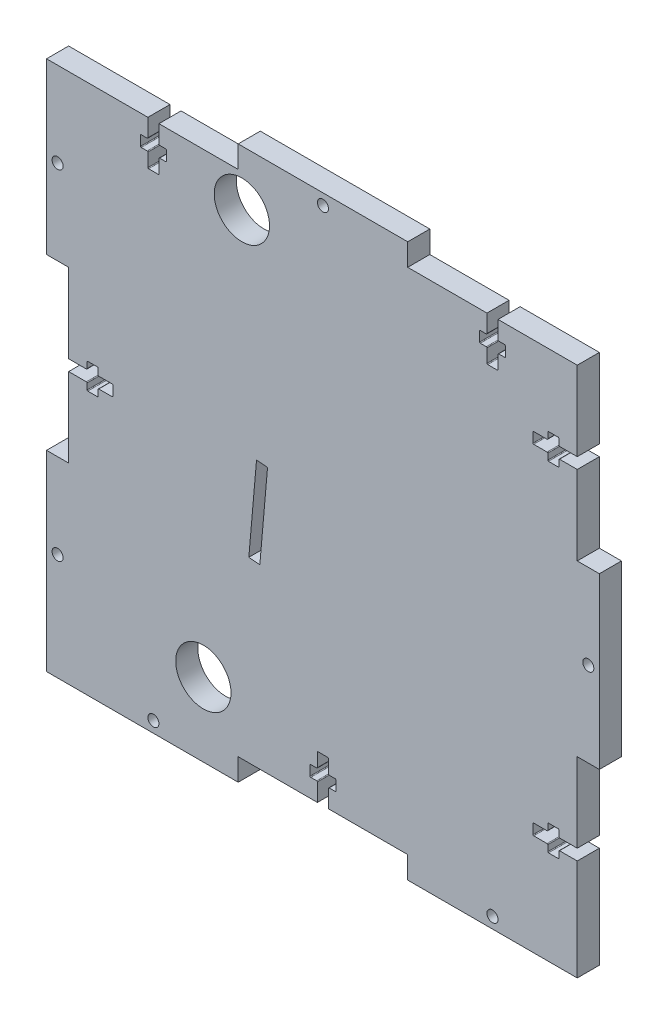
SolidWorks part; units mm, degrees
ref_plane "Front Plane" through (0, 0, 0) normal (0, 0, 1) x (1, 0, 0)
ref_plane "Top Plane" through (0, 0, 0) normal (0, 1, 0) x (1, 0, 0)
ref_plane "Right Plane" through (0, 0, 0) normal (1, 0, 0) x (0, 0, -1)
sketch "Sketch1" plane through (0, 0, 0) normal (0, 0, 1) x (1, 0, 0)
  line L0 (-69, 69) -> (-23, 69)
  line L5 (-75, -75) -> (75, -75) construction
  line L6 (-75, -75) -> (-75, 75) construction
  line L7 (-75, 75) -> (75, 75) construction
  line L8 (75, -75) -> (75, 75) construction
  line L9 (75, 23) -> (69, 23)
  line L10 (69, -23) -> (75, -23)
  line L11 (-69, -69) -> (69, -69) construction
  line L12 (-69, -69) -> (-69, 69) construction
  line L13 (-69, 69) -> (69, 69) construction
  line L14 (69, -69) -> (69, 69) construction
  line L15 (-69, -69) -> (69, 69) construction
  line L16 (69, -69) -> (69, -23)
  line L17 (-23, 69) -> (-23, 75)
  line L18 (-23, 75) -> (23, 75)
  line L19 (23, 75) -> (23, 69)
  line L20 (23, 69) -> (69, 69)
  line L21 (75, -23) -> (75, 23)
  line L22 (69, 23) -> (69, 69)
  line L23 (-75, 23) -> (-69, 23)
  line L24 (-69, 69) -> (-75, 69)
  line L25 (-75, 69) -> (-75, 23)
  line L26 (69, -69) -> (69, -75)
  line L27 (69, -75) -> (23, -75)
  line L28 (23, -75) -> (23, -69)
  line L29 (23, -69) -> (-23, -69)
  line L30 (-23, -69) -> (-23, -75)
  line L31 (-23, -75) -> (-69, -75)
  line L32 (-69, -75) -> (-69, -69) construction
  line L33 (-69, 23) -> (-69, -23)
  line L34 (-69, -23) -> (-75, -23)
  line L35 (-75, -23) -> (-75, -69)
  line L36 (-75, -69) -> (-69, -69) construction
  line L37 (-46, 69) -> (-46, -75) construction
  line L38 (-69, 69) -> (69, -69) construction
  line L39 (-75, -75) -> (-69, -75)
  line L40 (-75, -75) -> (-75, -69)
  point P0 (0, 0)
  point P6 (-7, -7)
  point P26 (0, -75)
  point P27 (-75, 0)
  dimension "D1" = 150
  dimension "D2" = 150
  dimension "D5" = 46
  dimension "D3" = 6
  dimension "D6" = 6
  dimension "D7" = 6
extrude "Box Side" add sketch "Sketch1" along normal blind 6
sketch "Sketch2" plane through (0, 0, 6) normal (0, 0, 1) x (1, 0, 0)
  line L0 (23, 72) -> (-23, 72) construction
  line L1 (23, 75) -> (23, 69) construction
  line L2 (-23, 69) -> (-23, 75) construction
  line L3 (-46, 69) -> (-46, -75) construction
  line L5 (0, 75) -> (0, 69) construction
  line L6 (-23, 75) -> (23, 75) construction
  line L7 (-69, 69) -> (69, 69) construction
  line L16 (-46, 69) -> (-46, -75) construction
  line L21 (0, -69) -> (0, 69) construction
  line L35 (-69, 69) -> (-23, 69) construction
  line L36 (-44.5, 69) -> (-44.5, 64.2)
  line L37 (-44.3, 64) -> (-42.7, 64)
  line L38 (-42.5, 63.8) -> (-42.5, 61.2)
  line L39 (-42.7, 61) -> (-44.3, 61)
  line L40 (-44.5, 60.8) -> (-44.5, 57.2)
  line L46 (-44.7, 57) -> (-47.3, 57)
  line L48 (-44.5, 69) -> (-47.5, 69)
  line L51 (-47.5, 60.8) -> (-47.5, 57.2)
  line L52 (-49.3, 61) -> (-47.7, 61)
  line L53 (-49.5, 63.8) -> (-49.5, 61.2)
  line L54 (-47.7, 64) -> (-49.3, 64)
  line L55 (-47.5, 69) -> (-47.5, 64.2)
  line L56 (47.5, 69) -> (47.5, 64.2)
  line L57 (47.7, 64) -> (49.3, 64)
  line L58 (49.5, 63.8) -> (49.5, 61.2)
  line L59 (49.3, 61) -> (47.7, 61)
  line L60 (47.5, 60.8) -> (47.5, 57.2)
  line L61 (44.5, 69) -> (47.5, 69)
  line L62 (44.7, 57) -> (47.3, 57)
  line L63 (44.5, 60.8) -> (44.5, 57.2)
  line L64 (42.7, 61) -> (44.3, 61)
  line L65 (42.5, 63.8) -> (42.5, 61.2)
  line L66 (44.3, 64) -> (42.7, 64)
  line L67 (44.5, 69) -> (44.5, 64.2)
  line L68 (-69, -69) -> (69, 69) construction
  line L69 (-69, -69) -> (69, 69) construction
  line L70 (75, 0) -> (69, 0) construction
  line L71 (72, 23) -> (72, -23) construction
  line L72 (69, 44.5) -> (64.2, 44.5)
  line L73 (64, 44.3) -> (64, 42.7)
  line L74 (63.8, 42.5) -> (61.2, 42.5)
  line L75 (61, 42.7) -> (61, 44.3)
  line L76 (60.8, 44.5) -> (57.2, 44.5)
  line L77 (57, 44.7) -> (57, 47.3)
  line L78 (69, 44.5) -> (69, 47.5)
  line L79 (60.8, 47.5) -> (57.2, 47.5)
  line L80 (61, 49.3) -> (61, 47.7)
  line L81 (63.8, 49.5) -> (61.2, 49.5)
  line L82 (64, 47.7) -> (64, 49.3)
  line L83 (69, 47.5) -> (64.2, 47.5)
  line L84 (69, -47.5) -> (64.2, -47.5)
  line L85 (64, -47.7) -> (64, -49.3)
  line L86 (63.8, -49.5) -> (61.2, -49.5)
  line L87 (61, -49.3) -> (61, -47.7)
  line L88 (60.8, -47.5) -> (57.2, -47.5)
  line L89 (69, -44.5) -> (69, -47.5)
  line L90 (57, -44.7) -> (57, -47.3)
  line L91 (60.8, -44.5) -> (57.2, -44.5)
  line L92 (61, -42.7) -> (61, -44.3)
  line L93 (63.8, -42.5) -> (61.2, -42.5)
  line L94 (64, -44.3) -> (64, -42.7)
  line L95 (69, -44.5) -> (64.2, -44.5)
  line L120 (-69, 69) -> (69, -69) construction
  line L121 (-69, 69) -> (69, -69) construction
  line L122 (-1.5, -69) -> (1.5, -69)
  line L123 (-23, -69) -> (23, -69) construction
  line L124 (1.5, -69) -> (1.5, -64.2)
  line L125 (1.7, -64) -> (3.3, -64)
  line L126 (3.5, -63.8) -> (3.5, -61.2)
  line L127 (3.3, -61) -> (1.7, -61)
  line L128 (1.5, -60.8) -> (1.5, -57.2)
  line L129 (1.3, -57) -> (-1.3, -57)
  line L130 (-1.5, -60.8) -> (-1.5, -57.2)
  line L131 (-3.3, -61) -> (-1.7, -61)
  line L132 (-3.5, -63.8) -> (-3.5, -61.2)
  line L133 (-1.7, -64) -> (-3.3, -64)
  line L134 (-1.5, -69) -> (-1.5, -64.2)
  line L135 (-69, -1.5) -> (-64.2, -1.5)
  line L136 (-64, -1.7) -> (-64, -3.3)
  line L137 (-63.8, -3.5) -> (-61.2, -3.5)
  line L138 (-61, -3.3) -> (-61, -1.7)
  line L139 (-60.8, -1.5) -> (-57.2, -1.5)
  line L140 (-57, 1.3) -> (-57, -1.3)
  line L141 (-60.8, 1.5) -> (-57.2, 1.5)
  line L142 (-61, 3.3) -> (-61, 1.7)
  line L143 (-63.8, 3.5) -> (-61.2, 3.5)
  line L144 (-64, 1.7) -> (-64, 3.3)
  line L145 (-69, 1.5) -> (-64.2, 1.5)
  line L146 (-69, -1.5) -> (-69, 1.5)
  line L147 (-69, -72) -> (-23, -72) construction
  line L148 (-23, 69) -> (-75, 69) construction
  line L149 (-23, -75) -> (-23, -69) construction
  line L150 (-69, -69) -> (-69, -75) construction
  line L151 (-75, -75) -> (-23, -75) construction
  circle A0 centre (0, 72) radius 1.5
  arc A1 (-44.5, 57.2) -> (-44.7, 57) centre (-44.7, 57.2) cw
  arc A2 (-44.3, 61) -> (-44.5, 60.8) centre (-44.3, 60.8) ccw
  arc A3 (-42.5, 61.2) -> (-42.7, 61) centre (-42.7, 61.2) cw
  arc A4 (-42.7, 64) -> (-42.5, 63.8) centre (-42.7, 63.8) cw
  arc A5 (-44.5, 64.2) -> (-44.3, 64) centre (-44.3, 64.2) ccw
  arc A6 (-47.5, 64.2) -> (-47.7, 64) centre (-47.7, 64.2) cw
  arc A7 (-49.3, 64) -> (-49.5, 63.8) centre (-49.3, 63.8) ccw
  arc A8 (-49.5, 61.2) -> (-49.3, 61) centre (-49.3, 61.2) ccw
  arc A9 (-47.7, 61) -> (-47.5, 60.8) centre (-47.7, 60.8) cw
  arc A10 (-47.5, 57.2) -> (-47.3, 57) centre (-47.3, 57.2) ccw
  arc A11 (47.5, 57.2) -> (47.3, 57) centre (47.3, 57.2) cw
  arc A12 (47.7, 61) -> (47.5, 60.8) centre (47.7, 60.8) ccw
  arc A13 (49.5, 61.2) -> (49.3, 61) centre (49.3, 61.2) cw
  arc A14 (49.3, 64) -> (49.5, 63.8) centre (49.3, 63.8) cw
  arc A15 (47.5, 64.2) -> (47.7, 64) centre (47.7, 64.2) ccw
  arc A16 (44.5, 64.2) -> (44.3, 64) centre (44.3, 64.2) cw
  arc A17 (42.7, 64) -> (42.5, 63.8) centre (42.7, 63.8) ccw
  arc A18 (42.5, 61.2) -> (42.7, 61) centre (42.7, 61.2) ccw
  arc A19 (44.3, 61) -> (44.5, 60.8) centre (44.3, 60.8) cw
  arc A20 (44.5, 57.2) -> (44.7, 57) centre (44.7, 57.2) ccw
  arc A21 (57.2, 44.5) -> (57, 44.7) centre (57.2, 44.7) cw
  arc A22 (61, 44.3) -> (60.8, 44.5) centre (60.8, 44.3) ccw
  arc A23 (61.2, 42.5) -> (61, 42.7) centre (61.2, 42.7) cw
  arc A24 (64, 42.7) -> (63.8, 42.5) centre (63.8, 42.7) cw
  arc A25 (64.2, 44.5) -> (64, 44.3) centre (64.2, 44.3) ccw
  arc A26 (64.2, 47.5) -> (64, 47.7) centre (64.2, 47.7) cw
  arc A27 (64, 49.3) -> (63.8, 49.5) centre (63.8, 49.3) ccw
  arc A28 (61.2, 49.5) -> (61, 49.3) centre (61.2, 49.3) ccw
  arc A29 (61, 47.7) -> (60.8, 47.5) centre (60.8, 47.7) cw
  arc A30 (57.2, 47.5) -> (57, 47.3) centre (57.2, 47.3) ccw
  arc A31 (57.2, -47.5) -> (57, -47.3) centre (57.2, -47.3) cw
  arc A32 (61, -47.7) -> (60.8, -47.5) centre (60.8, -47.7) ccw
  arc A33 (61.2, -49.5) -> (61, -49.3) centre (61.2, -49.3) cw
  arc A34 (64, -49.3) -> (63.8, -49.5) centre (63.8, -49.3) cw
  arc A35 (64.2, -47.5) -> (64, -47.7) centre (64.2, -47.7) ccw
  arc A36 (64.2, -44.5) -> (64, -44.3) centre (64.2, -44.3) cw
  arc A37 (64, -42.7) -> (63.8, -42.5) centre (63.8, -42.7) ccw
  arc A38 (61.2, -42.5) -> (61, -42.7) centre (61.2, -42.7) ccw
  arc A39 (61, -44.3) -> (60.8, -44.5) centre (60.8, -44.3) cw
  arc A40 (57.2, -44.5) -> (57, -44.7) centre (57.2, -44.7) ccw
  circle A41 centre (72, 0) radius 1.5
  arc A62 (1.5, -57.2) -> (1.3, -57) centre (1.3, -57.2) ccw
  arc A63 (1.7, -61) -> (1.5, -60.8) centre (1.7, -60.8) cw
  arc A64 (3.5, -61.2) -> (3.3, -61) centre (3.3, -61.2) ccw
  arc A65 (3.3, -64) -> (3.5, -63.8) centre (3.3, -63.8) ccw
  arc A66 (1.5, -64.2) -> (1.7, -64) centre (1.7, -64.2) cw
  arc A67 (-1.5, -64.2) -> (-1.7, -64) centre (-1.7, -64.2) ccw
  arc A68 (-3.3, -64) -> (-3.5, -63.8) centre (-3.3, -63.8) cw
  arc A69 (-3.5, -61.2) -> (-3.3, -61) centre (-3.3, -61.2) cw
  arc A70 (-1.7, -61) -> (-1.5, -60.8) centre (-1.7, -60.8) ccw
  arc A71 (-1.5, -57.2) -> (-1.3, -57) centre (-1.3, -57.2) cw
  arc A72 (-57.2, -1.5) -> (-57, -1.3) centre (-57.2, -1.3) ccw
  arc A73 (-61, -1.7) -> (-60.8, -1.5) centre (-60.8, -1.7) cw
  arc A74 (-61.2, -3.5) -> (-61, -3.3) centre (-61.2, -3.3) ccw
  arc A75 (-64, -3.3) -> (-63.8, -3.5) centre (-63.8, -3.3) ccw
  arc A76 (-64.2, -1.5) -> (-64, -1.7) centre (-64.2, -1.7) cw
  arc A77 (-64.2, 1.5) -> (-64, 1.7) centre (-64.2, 1.7) ccw
  arc A78 (-64, 3.3) -> (-63.8, 3.5) centre (-63.8, 3.3) cw
  arc A79 (-61.2, 3.5) -> (-61, 3.3) centre (-61.2, 3.3) cw
  arc A80 (-61, 1.7) -> (-60.8, 1.5) centre (-60.8, 1.7) ccw
  arc A81 (-57.2, 1.5) -> (-57, 1.3) centre (-57.2, 1.3) cw
  circle A82 centre (-46, -72) radius 1.5
  circle A83 centre (46, -72) radius 1.5
  circle A84 centre (-72, 46) radius 1.5
  circle A85 centre (-72, -46) radius 1.5
  point P6 (0, 72)
  point P38 (0, 0)
  point P56 (-46, 57)
  point P88 (46, 57)
  point P161 (57, 46)
  point P162 (57, -46)
  point P198 (0, -57)
  point P231 (-57, 0)
  point P234 (-42.5, 62.5)
  dimension "D1" = 3
  dimension "D2" = 0.2
  dimension "D8" = 0.2
  dimension "D14" = 3
  dimension "D4" = 3
  dimension "D7" = 1.5
  dimension "D10" = 3
  dimension "D12" = 1.5
  dimension "D9" = 12
  dimension "D11" = 5
  dimension "D13" = 7
  dimension "D3" = 12
  dimension "D5" = 7
  dimension "D6" = 5
extrude "Screw Cut-outs" cut sketch "Sketch2" against normal through all
sketch "Sketch3" plane through (0, 0, 6) normal (0, 0, 1) x (1, 0, 0)
  line L0 (-23, 69) -> (-44.5, 69) construction
  line L1 (-69, 23) -> (-69, 1.5) construction
  circle A0 centre (-22, 60) radius 7.5
  circle A1 centre (-32.45, -55) radius 7.5
  dimension "D1" = 15
  dimension "D4" = 15
  dimension "D2" = 9
  dimension "D3" = 47
  dimension "D5" = 10.45
  dimension "D6" = 115
extrude "Cut-Extrude1" cut sketch "Sketch3" against normal through all
sketch "Sketch4" plane through (0, 0, 6) normal (0, 0, 1) x (1, 0, 0)
  line L0 (-24.9996, 51) -> (49975.0004, 51) construction
  line L1 (-23, 69) -> (-44.5, 69) construction
  line L2 (-13.84, 51) -> (-13.84, 69) construction
  line L3 (69, 47.5) -> (69, 69) construction
  line L4 (-13.84, 51) -> (-25.7981, -85.6815) construction
  line L5 (-13.84, 51) -> (49795.8949, -4306.7871) construction
  line L6 (-10.8514, 50.7385) -> (-4368.6386, -49758.9964) construction
  line L7 (-20.1126, -20.6961) -> (-17.124, -20.9576)
  line L8 (-17.124, -20.9576) -> (-15.0323, 2.9511)
  line L9 (-15.0323, 2.9511) -> (-18.0209, 3.2125)
  line L10 (-18.0209, 3.2125) -> (-20.1126, -20.6961)
  dimension "D1" = 18
  dimension "D2" = 82.84
  dimension "D3" = 5
  dimension "D4" = 3
  dimension "D5" = 24
  dimension "D6" = 47.97
extrude "Cut-Extrude2" cut sketch "Sketch4" against normal through all
equation "\"filletRadius\"=0.2"
equation "\"D8@Sketch2\"=\"filletRadius\""
equation "\"D2@Sketch2\"=\"filletRadius\""
equation "\"fingerWidth\"= 46"
equation "\"D5@Sketch1\"=\"fingerWidth\""
equation "\"wallThickness\"= 6"
equation "\"D3@Sketch1\" = \"wallThickness\""
equation "\"D6@Sketch1\" = \"wallThickness\""
equation "\"D7@Sketch1\" = \"wallThickness\""
equation "\"D1@Box Side\" = \"wallThickness\""
equation "\"M3\"= 3"
equation "\"D14@Sketch2\"=\"M3\""
equation "\"D1@Sketch2\"=\"M3\""
equation "\"D12@Sketch2\"=\"M3\"/2"
equation "\"nutThickness\"=3"
equation "\"D10@Sketch2\" = \"nutThickness\""
equation "\"boltLength\"= 12"
equation "\"D9@Sketch2\" = \"boltLength\""
equation "\"distanceToNut\"= 5"
equation "\"D11@Sketch2\" = \"distanceToNut\""
equation "\"D13@Sketch2\" = \"nutWidth\""
equation "\"D7@Sketch2\"=\"M3\"/2"
equation "\"D4@Sketch2\" = \"nutThickness\""
equation "\"D3@Sketch2\" = \"boltLength\""
equation "\"D5@Sketch2\" = \"nutWidth\""
equation "\"D6@Sketch2\" = \"distanceToNut\""
equation "\"sideLength\"=150"
equation "\"D1@Sketch1\"=\"sideLength\""
equation "\"D2@Sketch1\"=\"sideLength\""
equation "\"nutWidth\"=7"
